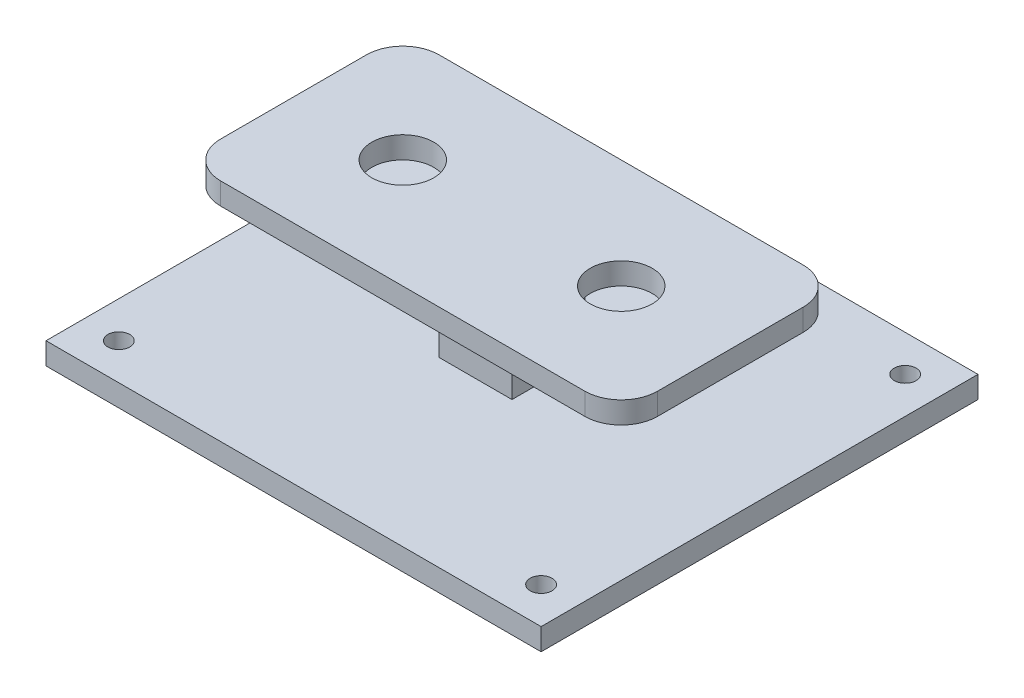
SolidWorks part; units mm, degrees
ref_plane "Alzado" through (0, 0, 0) normal (0, 0, 1) x (1, 0, 0)
ref_plane "Planta" through (0, 0, 0) normal (0, 1, 0) x (1, 0, 0)
ref_plane "Vista lateral" through (0, 0, 0) normal (1, 0, 0) x (0, 0, -1)
sketch "Croquis1" plane through (0, 0, 0) normal (0, 1, 0) x (1, 0, 0)
  line L1 (-34, 30) -> (34, 30)
  line L2 (-34, 30) -> (-34, -30)
  line L3 (-34, -30) -> (34, -30)
  line L4 (34, 30) -> (34, -30)
  line L5 (-34, 30) -> (34, -30) construction
  line L6 (-34, -30) -> (34, 30) construction
  circle A0 centre (-29, 25) radius 1.5
  circle A1 centre (29, 25) radius 1.5
  circle A2 centre (-29, -25) radius 1.5
  circle A3 centre (29, -25) radius 1.5
  point P9 (0, 0)
  dimension "D1" = 29
  dimension "D3" = 3
  dimension "D4" = 3
  dimension "D5" = 50
  dimension "D2" = 58
  dimension "D6" = 50
  dimension "D7" = 25
  dimension "D8" = 60
  dimension "D9" = 68
extrude "Saliente-Extruir2" add sketch "Croquis1" along normal blind 3
sketch "Croquis2" plane through (0, 3, 0) normal (0, 1, 0) x (1, 0, 0)
  line L1 (-2.5, 5) -> (2.5, 5)
  line L2 (-2.5, 5) -> (-2.5, -5)
  line L3 (-2.5, -5) -> (2.5, -5)
  line L4 (2.5, 5) -> (2.5, -5)
  line L5 (-2.5, 5) -> (2.5, -5) construction
  line L6 (-2.5, -5) -> (2.5, 5) construction
  point P0 (0, 0)
extrude "Saliente-Extruir3" add sketch "Croquis2" along normal blind 13
sketch "Croquis3" plane through (2.5, 0, 0) normal (1, 0, 0) x (0, 0, -1)
  line L0 (-5, 16) -> (5, 16) construction
  line L1 (-5, 11) -> (-5, 16)
  line L2 (-5, 16) -> (5, 16)
  line L3 (5, 16) -> (5, 11)
  circle A0 centre (0, 11) radius 5
  line M2 (5, 3) -> (5, 16)
  line M3 (5, 16) -> (-5, 16)
  line M4 (-5, 16) -> (-5, 3)
  dimension "D1" = 5
extrude "Cortar-Extruir1" cut sketch "Croquis3" against normal blind 13 contours A0 L2 M4 | A0 M2 M3
sketch "Croquis4" plane through (2.5, 0, 0) normal (1, 0, 0) x (0, 0, -1)
  circle A0 centre (0, 11) radius 1.5
extrude "Cortar-Extruir2" cut sketch "Croquis4" against normal blind 13
sketch "Croquis6" plane through (0, 0, -5) normal (0, 0, -1) x (-1, 0, 0)
  line L1 (-2.5, 3) -> (-1.75, 3)
  line L2 (-2.5, 3) -> (-2.5, 22.11)
  line L3 (-2.5, 22.11) -> (-1.75, 22.11)
  line L4 (-1.75, 3) -> (-1.75, 22.11)
  line L5 (2.5, 3) -> (1.75, 3)
  line L6 (2.5, 3) -> (2.5, 21.27)
  line L7 (2.5, 21.27) -> (1.75, 21.27)
  line L8 (1.75, 3) -> (1.75, 21.27)
extrude "Cortar-Extruir3" cut sketch "Croquis6" against normal blind 10
sketch "Croquis7" plane through (0, 0, -5) normal (0, 0, -1) x (-1, 0, 0)
  line L1 (-1.75, 3) -> (5.734, 3)
  line L2 (-1.75, 3) -> (-1.75, 21.6883)
  line L3 (-1.75, 21.6883) -> (5.734, 21.6883)
  line L4 (5.734, 3) -> (5.734, 21.6883)
extrude "Cortar-Extruir4" cut sketch "Croquis7" against normal blind 10
sketch "Croquis8" plane through (0, 3, 0) normal (0, 1, 0) x (1, 0, 0)
  line L1 (-5, 5) -> (5, 5)
  line L2 (-5, 5) -> (-5, -5)
  line L3 (-5, -5) -> (5, -5)
  line L4 (5, 5) -> (5, -5)
  line L5 (-5, 5) -> (5, -5) construction
  line L6 (-5, -5) -> (5, 5) construction
  point P0 (0, 0)
extrude "Saliente-Extruir4" add sketch "Croquis8" along normal blind 13
sketch "Croquis9" plane through (0, 16, 0) normal (0, 1, 0) x (1, 0, 0)
  line L1 (-30, 15) -> (30, 15)
  line L2 (-30, 15) -> (-30, -15)
  line L3 (-30, -15) -> (30, -15)
  line L4 (30, 15) -> (30, -15)
  line L5 (-30, 15) -> (30, -15) construction
  line L6 (-30, -15) -> (30, 15) construction
  point P0 (0, 0)
extrude "Saliente-Extruir5" add sketch "Croquis9" along normal blind 3
sketch "Croquis10" plane through (0, 19, 0) normal (0, 1, 0) x (1, 0, 0)
  circle A0 centre (-15, 0) radius 4.25
  circle A1 centre (15, 0) radius 4.25
  dimension "D1" = 15
  dimension "D2" = 15
extrude "Cortar-Extruir5" cut sketch "Croquis10" against normal blind 3
fillet "Redondeo1" radius 5 4 edges at (-30, 17.5, -15) (30, 17.5, 15) (30, 17.5, -15) (-30, 17.5, 15)
